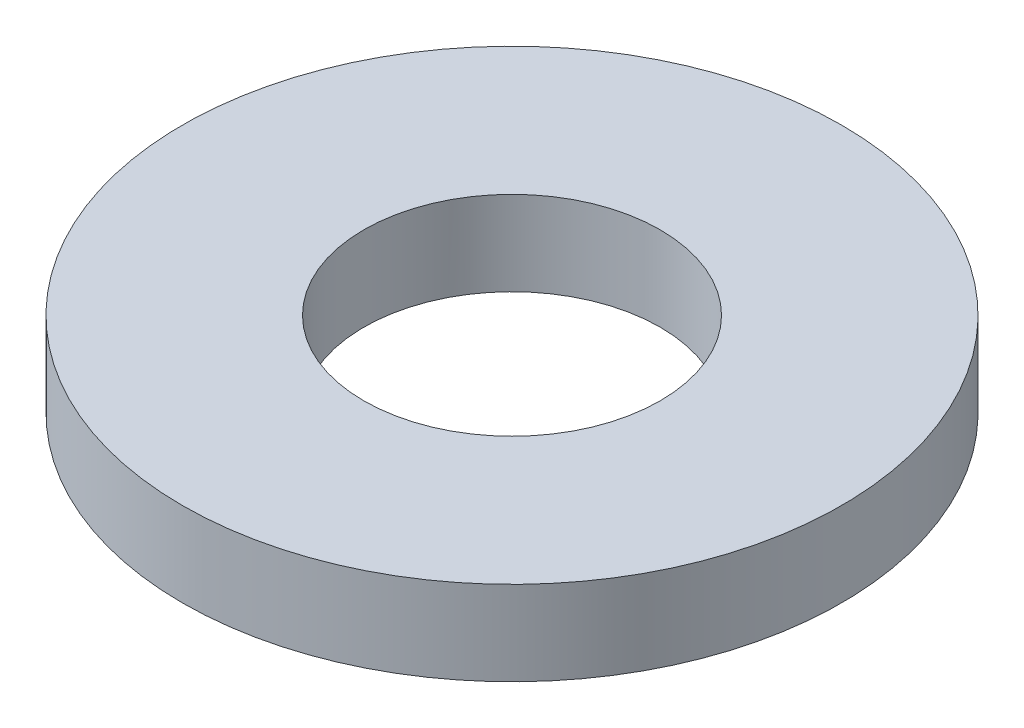
SolidWorks part; units mm, degrees
ref_plane "Front Plane" through (0, 0, 0) normal (0, 0, 1) x (1, 0, 0)
ref_plane "Top Plane" through (0, 0, 0) normal (0, 1, 0) x (1, 0, 0)
ref_plane "Right Plane" through (0, 0, 0) normal (1, 0, 0) x (0, 0, -1)
sketch "Sketch1" plane through (0, 0, 0) normal (0, 1, 0) x (1, 0, 0)
  circle A0 centre (0, 0) radius 7.9375
  circle A1 centre (0, 0) radius 3.5687
  dimension "D1" = 7.1374
extrude "Boss-Extrude2" add sketch "Sketch1" along normal blind 2.032 contours A0
sketch "Sketch3" plane through (0, 0, 0) normal (0, -1, 0) x (-1, 0, 0)
  circle A0 centre (0, 0) radius 3.5687
  dimension "D1" = 7.1374
extrude "Cut-Extrude1" cut sketch "Sketch3" against normal blind 3.302 contours A0
